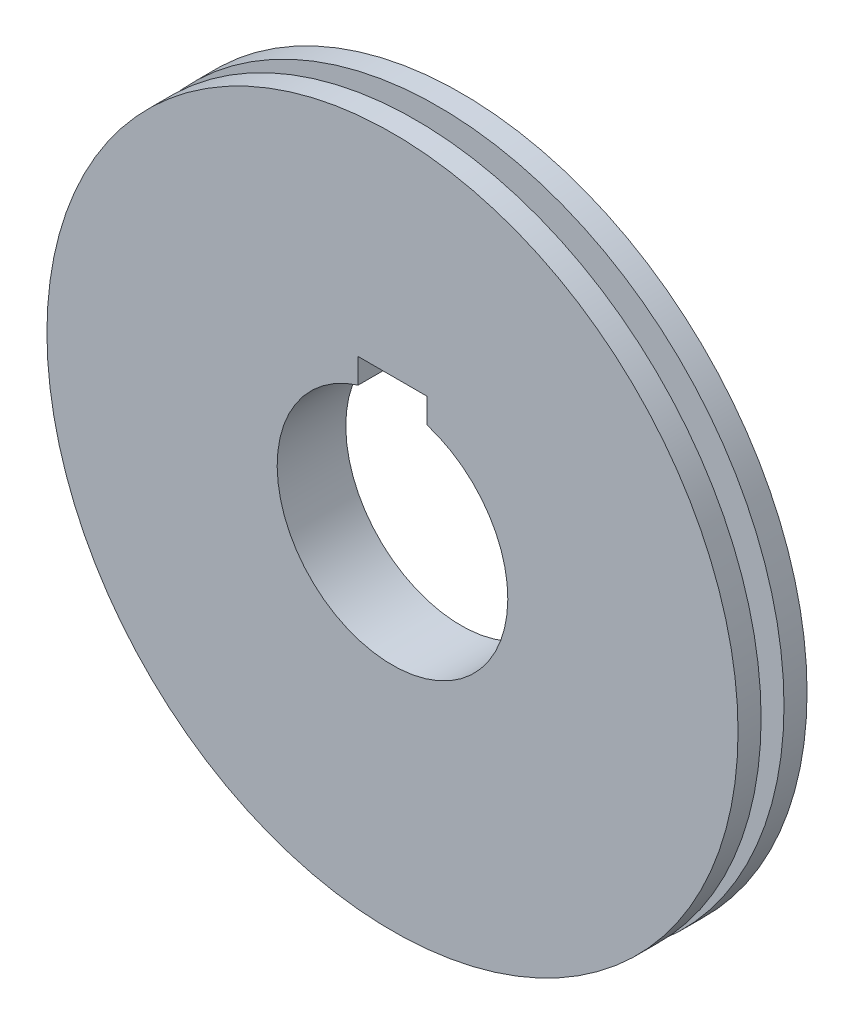
SolidWorks part; units mm, degrees
ref_plane "Front Plane" through (0, 0, 0) normal (0, 0, 1) x (1, 0, 0)
ref_plane "Top Plane" through (0, 0, 0) normal (0, 1, 0) x (1, 0, 0)
ref_plane "Right Plane" through (0, 0, 0) normal (1, 0, 0) x (0, 0, -1)
sketch "Sketch1" plane through (0, 0, 0) normal (0, 0, 1) x (1, 0, 0)
  circle A0 centre (0, 0) radius 60
  dimension "D1" = 120
extrude "Boss-Extrude2" add sketch "Sketch1" along normal blind 4
sketch "Sketch2" plane through (0, 0, 4) normal (0, 0, 1) x (1, 0, 0)
  circle A0 centre (0, 0) radius 20
  dimension "D1" = 40
extrude "Cut-Extrude1" cut sketch "Sketch2" against normal blind 20.9
sketch "Sketch3" plane through (0, 0, 4) normal (0, 0, 1) x (1, 0, 0)
  circle A0 centre (0, 0) radius 48.4681
extrude "Boss-Extrude3" add sketch "Sketch3" along normal blind 3.9
sketch "Sketch4" plane through (0, 0, 7.9) normal (0, 0, 1) x (1, 0, 0)
  circle A0 centre (0, 0) radius 59.9299
extrude "Boss-Extrude6" add sketch "Sketch4" along normal blind 4
sketch "Sketch8" plane through (0, 0, 11.9) normal (0, 0, 1) x (1, 0, 0)
  circle A0 centre (0, 0) radius 20
  dimension "D1" = 40
extrude "Cut-Extrude5" cut sketch "Sketch8" against normal blind 48
sketch "Sketch9" plane through (0, 0, 11.9) normal (0, 0, 1) x (1, 0, 0)
  line L0 (-5.95, 19.0944) -> (-5.95, 23.3944)
  line L1 (-5.95, 23.3944) -> (5.95, 23.3944)
  line L2 (5.95, 23.3944) -> (5.95, 19.0944)
  circle A0 centre (0, 0) radius 20 construction
  arc A1 (-5.95, 19.0944) -> (5.95, 19.0944) centre (0, 0) cw
  dimension "D1" = 4.3
  dimension "D2" = 4.3
  dimension "D3" = 11.9
extrude "Cut-Extrude6" cut sketch "Sketch9" against normal blind 48
